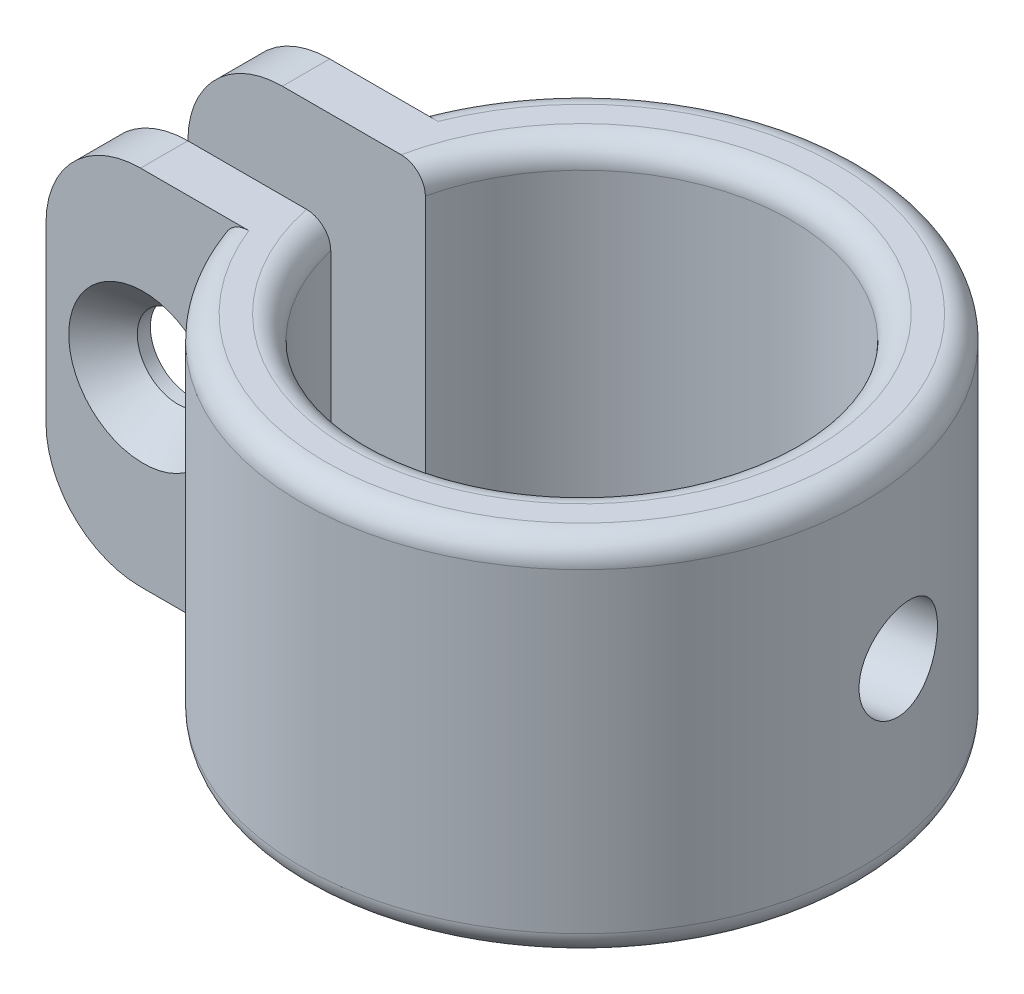
SolidWorks part; units mm, degrees
ref_plane "Front Plane" through (0, 0, 0) normal (0, 0, 1) x (1, 0, 0)
ref_plane "Top Plane" through (0, 0, 0) normal (0, 1, 0) x (1, 0, 0)
ref_plane "Right Plane" through (0, 0, 0) normal (1, 0, 0) x (0, 0, -1)
sketch "Sketch1" plane through (0, 0, 0) normal (0, 0, 1) x (1, 0, 0)
  line L0 (0, 0) -> (0, 130) construction
  line L1 (-8.85, 130) -> (8.85, 130) construction
  line L2 (-3.8, 7) -> (3.8, 7) construction
  line L3 (-3.8, 12.6) -> (3.8, 12.6) construction
  line L4 (-8.875, 30) -> (8.875, 30) construction
  line L5 (-7.05, 21) -> (7.05, 21) construction
  line L6 (-7.6, 30) -> (7.6, 30) construction
  line L7 (3.8, 7) -> (2.8, 7) construction
  line L8 (3.8, 7) -> (3.8, 12.6) construction
  line L9 (3.8, 12.6) -> (7.05, 21) construction
  line L10 (7.05, 21) -> (7.6, 30) construction
  line L11 (7.6, 30) -> (8.875, 30) construction
  line L12 (-8.85, 129.5) -> (8.85, 129.5) construction
  line L13 (8.875, 30) -> (8.85, 129.5) construction
  line L14 (8.85, 129.5) -> (8.85, 29.121) construction
  line L15 (8.85, 52.2759) -> (11.85, 52.2759)
  line L16 (8.85, 52.2759) -> (8.85, 36.9424)
  line L17 (8.85, 36.9424) -> (11.85, 36.9424)
  line L18 (11.85, 52.2759) -> (11.85, 36.9424)
  line L19 (8.85, 52.2759) -> (11.85, 36.9424) construction
  line L20 (8.85, 36.9424) -> (11.85, 52.2759) construction
  spline S0 degree 2 poles (0, 0) (0.935, 0.0329) (2.8, 7) knots 0 0 0 1 1 1 construction
  spline S1 degree 2 poles (0, 130) (7.4447, 130.0874) (8.85, 129.5) knots 0 0 0 1 1 1 construction
  point P4 (0, 130)
  point P7 (0, 7)
  point P10 (0, 12.6)
  point P13 (0, 30)
  point P16 (0, 21)
  point P20 (0, 30)
  point P23 (0, 129.5)
  point P26 (10.35, 44.6092)
  dimension "D1" = 130
  dimension "D2" = 17.7
  dimension "D3" = 30
  dimension "D4" = 7
  dimension "D5" = 5.6
  dimension "D6" = 9
  dimension "D7" = 17.75
  dimension "D8" = 7.6
  dimension "D9" = 14.1
  dimension "D10" = 15.2
  dimension "D11" = 1
  dimension "D12" = 0.5
  dimension "D13" = 3
revolve "Revolve1" add sketch "Sketch1" angle 360 about L0
fillet "Fillet1" radius 1 4 edges at (0, 36.9424, -8.85) (0, 36.9424, -11.85) (0, 52.2759, -11.85) (0, 52.2759, -8.85)
sketch "Sketch3" plane through (0, 0, 0) normal (0, 0, 1) x (1, 0, 0)
  line L1 (-14.4441, 52.4387) -> (-7.7683, 52.4387)
  line L2 (-14.4441, 52.4387) -> (-14.4441, 36.7797)
  line L3 (-14.4441, 36.7797) -> (-7.7683, 36.7797)
  line L4 (-7.7683, 52.4387) -> (-7.7683, 36.7797)
  line L5 (-14.4441, 52.4387) -> (-7.7683, 36.7797) construction
  line L6 (-14.4441, 36.7797) -> (-7.7683, 52.4387) construction
  point P0 (-11.1062, 44.6092)
extrude "Cut-Extrude1" cut sketch "Sketch3" against normal mid plane 4
sketch "Sketch4" plane through (0, 0, 0) normal (0, 0, 1) x (1, 0, 0)
  line L0 (-9.6448, 36.9424) -> (-10.6641, 36.9424) construction
  line L1 (-11.68, 37.9424) -> (-11.68, 51.2759) construction
  line L2 (-10.6641, 52.2759) -> (-9.6448, 52.2759) construction
  line L3 (-8.621, 51.2759) -> (-8.621, 37.9424) construction
  line L4 (-9.6448, 36.9424) -> (-10.6641, 36.9424)
  line L5 (-11.68, 37.9424) -> (-11.68, 51.2759) construction
  line L6 (-10.6641, 52.2759) -> (-9.6448, 52.2759)
  line L7 (-8.621, 51.2759) -> (-8.621, 37.9424)
  line L9 (-10.6641, 36.9424) -> (-14.6641, 36.9424)
  line L10 (-10.6641, 36.9424) -> (-10.6641, 52.2759) construction
  line L11 (-10.6641, 52.2759) -> (-14.6641, 52.2759)
  line L12 (-18.6641, 40.9424) -> (-18.6641, 48.2759)
  arc A0 (-14.6641, 36.9424) -> (-18.6641, 40.9424) centre (-14.6641, 40.9424) cw
  arc A1 (-14.6641, 52.2759) -> (-18.6641, 48.2759) centre (-14.6641, 48.2759) ccw
  spline S0 degree 3 poles (-447.6176, -860.5447) (-56.2528, 71.72) (-6.2962, 43.154) (-8.7528, 37.435) (-8.8301, 37.3236) (-9.0196, 37.1405) (-9.1334, 37.0669) (-14.3855, 34.9541) (-40.3891, 73.6987) (938, 356.2069) knots -11.289371 -11.289371 -11.289371 -11.289371 0.25 0.25 0.5 0.5 0.75 0.75 11.22469 11.22469 11.22469 11.22469 only from (-8.621, 37.9424) to (-9.6448, 36.9424) construction
  spline S1 degree 3 poles (-924.0156, 444.1126) (25.3407, 96.5932) (-4.6872, 34.4478) (-11.1724, 37.0667) (-11.2849, 37.1398) (-11.4742, 37.3246) (-11.55, 37.4352) (-14.2587, 43.8245) (48.842, 74.2817) (448.2651, -849.9936) knots -12.755364 -12.755364 -12.755364 -12.755364 0.25 0.25 0.5 0.5 0.75 0.75 13.618646 13.618646 13.618646 13.618646 only from (-10.6641, 36.9424) to (-11.68, 37.9424) construction
  spline S2 degree 3 poles (345.3971, 985.3502) (23.9467, 20.1452) (-13.6971, 46.7356) (-11.5497, 51.7833) (-11.4732, 51.8948) (-11.2852, 52.0781) (-11.1721, 52.1518) (-5.0915, 54.6065) (23.4409, 0.4718) (-938.1562, -321.5656) knots -9.943953 -9.943953 -9.943953 -9.943953 0.25 0.25 0.5 0.5 0.75 0.75 12.952579 12.952579 12.952579 12.952579 only from (-11.68, 51.2759) to (-10.6641, 52.2759) construction
  spline S3 degree 3 poles (860.914, -439.7859) (-61.804, 11.2347) (-13.6861, 56.5845) (-8.8294, 51.8941) (-8.7529, 51.7837) (-6.3944, 46.2941) (-52.555, 19.4329) (-360.7177, 987.2175) knots -11.920418 -11.920418 -11.920418 -11.920418 0.5 0.5 0.75 0.75 11.782189 11.782189 11.782189 11.782189 only from (-9.6448, 52.2759) to (-8.621, 51.2759) construction
  spline S4 degree 3 poles (-8.621, 37.9424) (-8.621, 37.8096) (-8.6486, 37.6775) (-8.7528, 37.435) (-8.8301, 37.3236) (-9.0196, 37.1405) (-9.1334, 37.0669) (-9.3782, 36.9684) (-9.5125, 36.9424) (-9.6448, 36.9424) knots 0 0 0 0 0.25 0.25 0.5 0.5 0.75 0.75 1 1 1 1
  spline S5 degree 3 poles (-10.6641, 36.9424) (-10.7968, 36.9424) (-10.9278, 36.9679) (-11.1724, 37.0667) (-11.2849, 37.1398) (-11.4742, 37.3246) (-11.55, 37.4352) (-11.6532, 37.6787) (-11.68, 37.8096) (-11.68, 37.9424) knots 0 0 0 0 0.25 0.25 0.5 0.5 0.75 0.75 1 1 1 1 construction
  spline S6 degree 3 poles (-11.68, 51.2759) (-11.68, 51.4078) (-11.6525, 51.5417) (-11.5497, 51.7833) (-11.4732, 51.8948) (-11.2852, 52.0781) (-11.1721, 52.1518) (-10.9279, 52.2503) (-10.7964, 52.2759) (-10.6641, 52.2759) knots 0 0 0 0 0.25 0.25 0.5 0.5 0.75 0.75 1 1 1 1 construction
  spline S7 degree 3 poles (-9.6448, 52.2759) (-9.3788, 52.2759) (-9.1169, 52.1717) (-8.8294, 51.8941) (-8.7529, 51.7837) (-8.6484, 51.5405) (-8.621, 51.4078) (-8.621, 51.2759) knots 0 0 0 0 0.5 0.5 0.75 0.75 1 1 1 1
  point P14 (-18.6641, 52.2759)
  dimension "D2" = 4
  dimension "D1" = 8
extrude "Boss-Extrude1" add sketch "Sketch4" against normal blind 2 from offset 2 contours A0 L12 A1 L11 L6 S7 L7 S4 L4 L9 offset against normal yes
mirror "Mirror1" about plane through (0, 0, 0) normal (0, 0, 1) of "Boss-Extrude1"
hole_wizard "CSK for M3 Flat Head Machine Screw1" positions "Sketch5" profile "Sketch6" countersink size "M3" standard "ANSI Metric"
sketch "Sketch5" plane through (0, 0, 4) normal (0, 0, 1) x (1, 0, 0)
  point P0 (-14.5523, 44.6668)
  point P3 (-14.5523, 44.6668)
sketch "Sketch6" plane through (-14.5523, 44.6668, 4) normal (1, 0, 0) x (0, -1, 0)
  line L0 (0, 0) -> (0, 11.0715)
  line L1 (0, 11.0715) -> (1.7, 10.05)
  line L2 (1.7, 10.05) -> (1.7, 1.45)
  line L3 (1.7, 1.45) -> (3.15, 0)
  line L5 (3.15, 0) -> (0, 0)
  line L6 (-1.7, 1.45) -> (-3.15, 0) construction
  line L10 (0, 11.0715) -> (-1.7, 10.05) construction
  line L11 (0, -6.35) -> (0, 107.95) construction
  dimension "Hole Dia." = 3.4
  dimension "Hole Depth" = 10.05
  dimension "Near C'Sink Dia." = 6.3
  dimension "Near C'Sink Angle" = 90
  dimension "Drill Angle" = 118
sketch "Sketch7" plane through (0, 0, -4) normal (0, 0, -1) x (-1, 0, 0)
  line L1 (17.3473, 46.2921) -> (14.5423, 47.9)
  line L2 (14.5423, 47.9) -> (11.7473, 46.2747)
  line L3 (11.7473, 46.2747) -> (11.7573, 43.0416)
  line L4 (11.7573, 43.0416) -> (14.5623, 41.4337)
  line L5 (14.5623, 41.4337) -> (17.3573, 43.0589)
  line L6 (17.3573, 43.0589) -> (17.3473, 46.2921)
  circle A0 centre (14.5523, 44.6668) radius 2.8 construction
  dimension "D1" = 5.6
extrude "Cut-Extrude2" cut sketch "Sketch7" against normal blind 1
sketch "Sketch8" plane through (0, 0, -2) normal (0, 0, 1) x (1, 0, 0)
  line L0 (11.85, 51.2759) -> (11.85, 37.9424) construction
  point P4 (11.85, 44.6092)
ref_point "Point1"
hole_wizard "Ø4.0mm Dowel Hole1" positions "3DSketch1" profile "Sketch2" hole size "Ø4.0" standard "ANSI Metric"
sketch3d "3DSketch1"
  point P0 (11.7012, 44.5408, -1.8719)
sketch "Sketch2" plane through (11.7012, 44.5408, -1.8719) normal (0, 1, 0) x (-0.158, 0, -0.9874)
  line L0 (0, 0) -> (0, 11.2517)
  line L1 (0, 11.2517) -> (2, 10.05)
  line L2 (2, 10.05) -> (2, 0)
  line L5 (2, 0) -> (0, 0)
  line L10 (0, 11.2517) -> (-2, 10.05) construction
  line L11 (0, -6.35) -> (0, 107.95) construction
  dimension "Hole Dia." = 4
  dimension "Hole Depth" = 10.05
  dimension "Drill Angle" = 118
